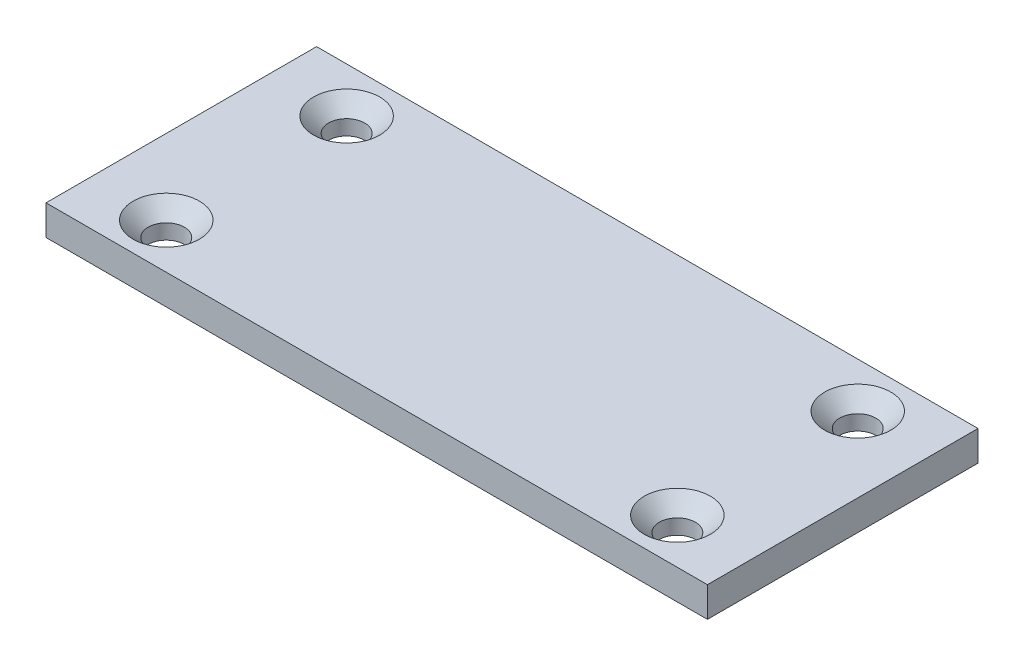
SolidWorks part; units mm, degrees
ref_plane "Front Plane" through (0, 0, 0) normal (0, 0, 1) x (1, 0, 0)
ref_plane "Top Plane" through (0, 0, 0) normal (0, 1, 0) x (1, 0, 0)
ref_plane "Right Plane" through (0, 0, 0) normal (1, 0, 0) x (0, 0, -1)
sketch "Sketch1" plane through (0, 0, 0) normal (0, 1, 0) x (1, 0, 0)
  line L1 (-22, -9) -> (22, -9)
  line L2 (-22, -9) -> (-22, 9)
  line L3 (-22, 9) -> (22, 9)
  line L4 (22, -9) -> (22, 9)
  line L5 (-22, -9) -> (22, 9) construction
  line L6 (-22, 9) -> (22, -9) construction
  point P0 (0, 0)
  dimension "D1" = 44
  dimension "D2" = 18
extrude "Boss-Extrude1" add sketch "Sketch1" along normal blind 2
sketch "Sketch5" plane through (0, 2, 0) normal (0, 1, 0) x (1, 0, 0)
  line L0 (22, 9) -> (-22, 9) construction
  line L1 (-22, -9) -> (22, -9) construction
  line L2 (-22, 9) -> (-22, -9) construction
  line L3 (22, -9) -> (22, 9) construction
  point P0 (-17, 6)
  point P2 (17, 6)
  point P4 (-17, -6)
  point P6 (17, -6)
  dimension "D1" = 3
  dimension "D2" = 3
  dimension "D3" = 3
  dimension "D4" = 3
  dimension "D5" = 5
  dimension "D6" = 5
  dimension "D7" = 5
  dimension "D8" = 5
hole_wizard "CSK for M2 Flat Head Machine Screw1" positions "Sketch5" profile "Sketch6" countersink size "M2" standard "ANSI Metric"
sketch "Sketch6" plane through (-17, 2, -6) normal (1, 0, 0) x (0, 0, 1)
  line L0 (0, 0) -> (0, 10.721)
  line L1 (0, 10.721) -> (1.2, 10)
  line L2 (1.2, 10) -> (1.2, 1)
  line L3 (1.2, 1) -> (2.2, 0)
  line L5 (2.2, 0) -> (0, 0)
  line L6 (-1.2, 1) -> (-2.2, 0) construction
  line L10 (0, 10.721) -> (-1.2, 10) construction
  line L11 (0, -6.35) -> (0, 107.95) construction
  dimension "Hole Dia." = 2.4
  dimension "Hole Depth" = 10
  dimension "Near C'Sink Dia." = 4.4
  dimension "Near C'Sink Angle" = 90
  dimension "Drill Angle" = 118
